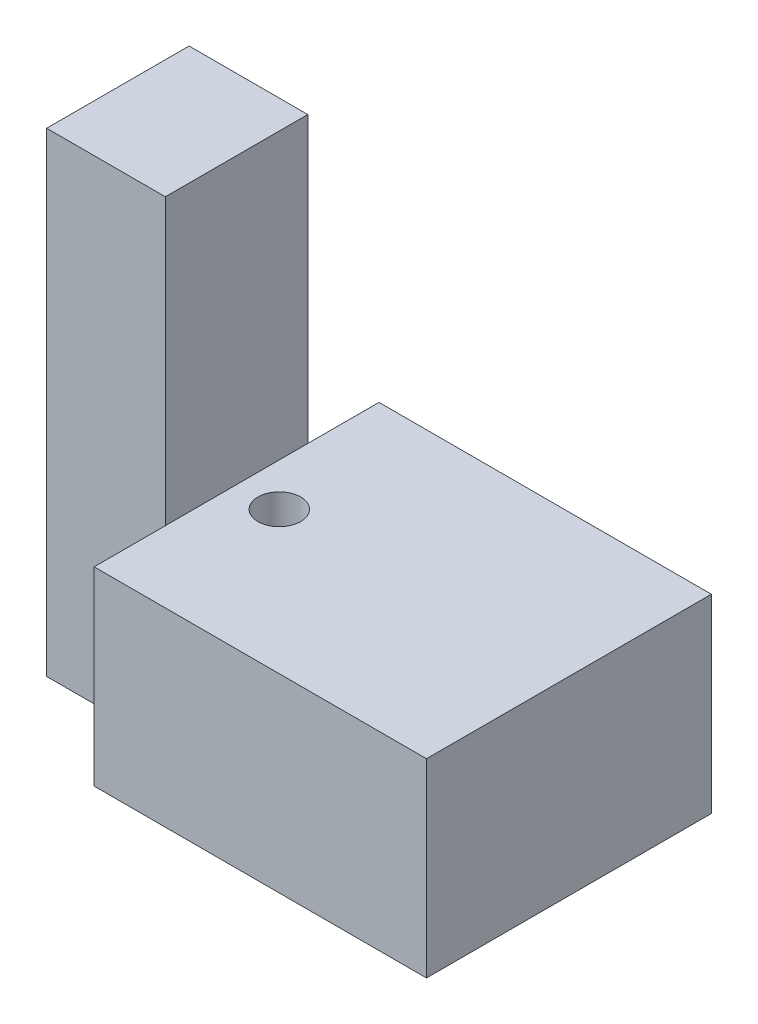
SolidWorks part; units mm, degrees
ref_plane "Plan de face" through (0, 0, 0) normal (0, 0, 1) x (1, 0, 0)
ref_plane "Plan de dessus" through (0, 0, 0) normal (0, 1, 0) x (1, 0, 0)
ref_plane "Plan de droite" through (0, 0, 0) normal (1, 0, 0) x (0, 0, -1)
sketch "Esquisse1" plane through (0, 0, 0) normal (0, 0, 1) x (1, 0, 0)
  line L1 (-69.1351, 23.2641) -> (0.8649, 23.2641)
  line L2 (-69.1351, 23.2641) -> (-69.1351, -16.7359)
  line L3 (-69.1351, -16.7359) -> (0.8649, -16.7359)
  line L4 (0.8649, 23.2641) -> (0.8649, -16.7359)
  dimension "D1" = 70
  dimension "D2" = 40
extrude "Boss.-Extru.1" add sketch "Esquisse1" along normal blind 60
sketch "Esquisse2" plane through (0, 23.2641, 0) normal (0, 1, 0) x (1, 0, 0)
  line L0 (-69.1351, -60) -> (-69.1351, 0) construction
  circle A0 centre (-60.1351, -30) radius 4.5
  point P2 (-69.1351, -30)
  dimension "D1" = 9
  dimension "D2" = 9
extrude "Enlèv. mat.-Extru.1" cut sketch "Esquisse2" against normal blind 60
sketch "Esquisse3" plane through (-69.1351, 0, 0) normal (-1, 0, 0) x (0, 0, 1)
  line L0 (60, 23.2641) -> (0, 23.2641) construction
  line L1 (15, 23.2641) -> (45, 23.2641)
  line L2 (15, 23.2641) -> (15, -16.7359)
  line L3 (15, -16.7359) -> (45, -16.7359)
  line L4 (45, 23.2641) -> (45, -16.7359)
  line L5 (60, -16.7359) -> (0, -16.7359) construction
  dimension "D1" = 15
  dimension "D2" = 15
  dimension "D3" = 30
extrude "Boss.-Extru.2" add sketch "Esquisse3" along normal blind 25
sketch "Esquisse4" plane through (0, 23.2641, 0) normal (0, 1, 0) x (1, 0, 0)
  line L1 (-94.1351, -15) -> (-69.1351, -15)
  line L2 (-94.1351, -15) -> (-94.1351, -45)
  line L3 (-94.1351, -45) -> (-69.1351, -45)
  line L4 (-69.1351, -15) -> (-69.1351, -45)
extrude "Boss.-Extru.3" add sketch "Esquisse4" along normal blind 60
